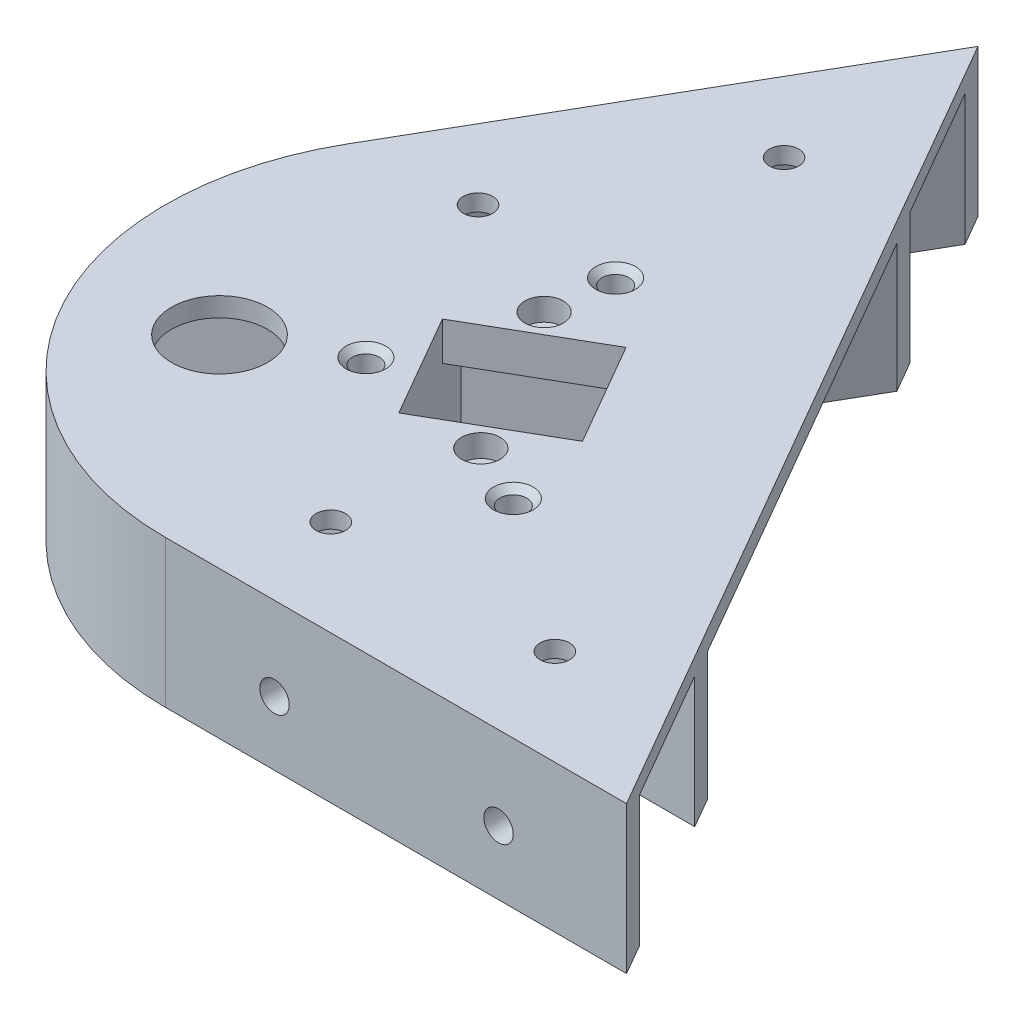
SolidWorks part; units mm, degrees
other "Markup1"
sketch "Sketch26" plane through (25.6218, 0, -129.9038) normal (-0.1134, -0.9932, -0.0259) x (0.9576, -0.1162, 0.2636)
ref_plane "Front Plane" through (0, 0, 0) normal (0, 0, 1) x (1, 0, 0)
ref_plane "Top Plane" through (0, 0, 0) normal (0, 1, 0) x (1, 0, 0)
ref_plane "Right Plane" through (0, 0, 0) normal (1, 0, 0) x (0, 0, -1)
sketch "Sketch1" plane through (0, 0, 0) normal (0, 1, 0) x (1, 0, 0)
  line L0 (0, 0) -> (150, 0)
  line L1 (0, 0) -> (75, 129.9038)
  line L2 (75, 129.9038) -> (150, 0)
  dimension "D1" = 60
  dimension "D2" = 150
  dimension "D3" = 60
extrude "Boss-Extrude1" add sketch "Sketch1" along normal blind 23
sketch "Sketch2" plane through (0, 0, 0) normal (0, 1, 0) x (1, 0, 0)
  line L0 (0, 0) -> (150, 0) construction
  line L1 (74, 5) -> (174, 5) construction
  line L2 (74, 5) -> (74, 25) construction
  line L3 (74, 25) -> (174, 25) construction
  line L4 (174, 5) -> (174, 25) construction
  line L5 (41.3301, 61.5859) -> (91.3301, 148.1884) construction
  line L6 (91.3301, 148.1884) -> (108.6506, 138.1884) construction
  line L7 (108.6506, 138.1884) -> (58.6506, 51.5859) construction
  line L8 (58.6506, 51.5859) -> (41.3301, 61.5859) construction
  line L9 (75, 129.9038) -> (0, 0) construction
  line L10 (108.9238, 138.2616) -> (58.7238, 51.3127)
  line L11 (58.7238, 51.3127) -> (41.0569, 61.5127)
  line L12 (41.0569, 61.5127) -> (91.2569, 148.4616)
  line L13 (91.2569, 148.4616) -> (108.9238, 138.2616)
  line L14 (73.8, 25.2) -> (174.2, 25.2)
  line L15 (174.2, 4.8) -> (174.2, 25.2)
  line L16 (73.8, 4.8) -> (174.2, 4.8)
  line L17 (73.8, 4.8) -> (73.8, 25.2)
  dimension "D1" = 20
  dimension "D2" = 5
  dimension "D3" = 74
  dimension "D4" = 20
  dimension "D5" = 74
  dimension "D6" = 5
  dimension "D7" = 100
  dimension "D8" = 100
  dimension "D9" = 0.2
  dimension "D10" = 0.2
extrude "Cut-Extrude2" cut sketch "Sketch2" along normal blind 20.4
sketch "Sketch4" plane through (0, 0, 0) normal (0, 1, 0) x (1, 0, 0)
  line L4 (135.4508, 25.2) -> (89.5492, 104.7038) construction
  line L5 (41.1219, 35.2887) -> (0, 0) construction
  line L6 (0, 0) -> (52.9457, 91.7047) construction
  line L7 (68.4424, 27.9682) -> (51.1219, 17.9682) construction
  line L8 (68.4424, 27.9682) -> (58.4424, 45.2887) construction
  line L9 (58.4424, 45.2887) -> (41.1219, 35.2887) construction
  line L10 (51.1219, 17.9682) -> (41.1219, 35.2887) construction
  line L11 (68.4424, 27.9682) -> (41.1219, 35.2887) construction
  line L12 (58.4424, 45.2887) -> (51.1219, 17.9682) construction
  line L13 (58.5156, 45.5619) -> (40.8487, 35.3619)
  line L14 (75, 129.9038) -> (0, 0) construction
  line L15 (0, 0) -> (130.8784, 0) construction
  line L16 (0, 0) -> (150, 0) construction
  line L17 (51.0487, 17.695) -> (40.8487, 35.3619)
  line L18 (68.7156, 27.895) -> (51.0487, 17.695)
  line L19 (68.7156, 27.895) -> (58.5156, 45.5619)
  line L20 (51.1219, 17.9682) -> (0, 0) construction
  point P0 (54.7821, 31.6285)
  dimension "D1" = 20
  dimension "D2" = 20
  dimension "D3" = 21.269
  dimension "D4" = 0.2
  dimension "D5" = 54.1877
  dimension "D6" = 19.365
extrude "Cut-Extrude3" cut sketch "Sketch4" along normal blind 20
sketch "Sketch7" plane through (0, 0, 0) normal (-0.866, 0, -0.5) x (-0.5, 0, 0.866)
  line L0 (-150, 0) -> (0, 0) construction
  line L1 (-150, 23) -> (-150, 0) construction
  circle A0 centre (-130, 10) radius 2.3
  circle A1 centre (-95, 10) radius 2.3
  dimension "D1" = 4.6
  dimension "D2" = 10
  dimension "D3" = 20
  dimension "D4" = 35
extrude "Cut-Extrude6" cut sketch "Sketch7" against normal blind 10
sketch "Sketch8" plane through (0, 0, 0) normal (0, 0, 1) x (1, 0, 0)
  line L0 (150, 23) -> (150, 0) construction
  line L1 (0, 0) -> (150, 0) construction
  circle A0 centre (130, 10) radius 2.3
  circle A1 centre (95, 10) radius 2.3
  dimension "D1" = 4.6
  dimension "D2" = 20
  dimension "D3" = 10
  dimension "D4" = 35
extrude "Cut-Extrude7" cut sketch "Sketch8" against normal blind 10
ref_plane "Plane1" through (42.4846, 0, -24.5285) normal (0.866, 0, -0.5) x (-0.5, 0, -0.866)
fillet "Fillet3" radius 45 1 edges at (0, 11.5, 0)
sketch "Sketch22" plane through (0, 0, 0) normal (0, -1, 0) x (1, 0, 0)
  line L0 (83.3534, -28.1478) -> (66.0534, -58.1122)
  line L1 (66.0534, -58.1122) -> (84.2399, -68.6122)
  line L2 (84.2399, -68.6122) -> (101.5399, -38.6478)
  line L3 (101.5399, -38.6478) -> (83.3534, -28.1478)
  line L5 (135.4508, -25.2) -> (89.5492, -104.7038) construction
  dimension "D1" = 86.26
  dimension "D2" = 17.3
  dimension "D3" = 17.3
  dimension "D4" = 21
extrude "Cut-Extrude11" cut sketch "Sketch22" against normal through all both and the other way through all
sketch "Sketch21" plane through (0, 0, 0) normal (0, -1, 0) x (1, 0, 0)
  line L0 (132.6795, -30) -> (109.9968, -30)
  line L1 (109.9968, -30) -> (80.9791, -80.26)
  line L2 (80.9791, -80.26) -> (92.3205, -99.9038)
  line L3 (92.3205, -99.9038) -> (132.6795, -30)
  line L4 (135.4508, -25.2) -> (89.5492, -104.7038) construction
  line L5 (135.4508, -25.2) -> (73.8, -25.2) construction
  line L7 (58.7238, -51.3127) -> (89.5492, -104.7038) construction
  line L8 (58.7238, -51.3127) -> (89.5492, -104.7038) construction
  line L9 (84.2399, -68.6122) -> (101.5399, -38.6478) construction
  dimension "D1" = 3
  dimension "D2" = 4.8
  dimension "D3" = 4.8
extrude "Cut-Extrude10" cut sketch "Sketch21" against normal offset from surface (20 mm away) 3 up to face at (83.7966, 23, -48.38)
sketch "Sketch32" plane through (0, 0, -30) normal (0, 0, -1) x (-1, 0, 0)
  line L0 (-132.6795, 10) -> (-109.9968, 10) construction
  line L1 (-132.6795, 20) -> (-132.6795, 0) construction
  line L2 (-109.9968, 20) -> (-109.9968, 0) construction
  circle A0 centre (-121.3381, 10) radius 2.3
  dimension "D1" = 4.6
extrude "Cut-Extrude18" cut sketch "Sketch32" against normal blind 10
sketch "Sketch33" plane through (25.9808, 0, 15) normal (0.866, 0, 0.5) x (0.5, 0, -0.866)
  line L0 (109.9968, 10) -> (132.6795, 10) construction
  line L1 (109.9968, 20) -> (109.9968, 0) construction
  line L2 (132.6795, 20) -> (132.6795, 0) construction
  circle A0 centre (121.3381, 10) radius 2.3
  dimension "D1" = 4.6
extrude "Cut-Extrude19" cut sketch "Sketch33" against normal blind 10
sketch "Sketch34" plane through (45.9487, 0, -26.5285) normal (0.866, 0, -0.5) x (-0.5, 0, -0.866)
  line L0 (-10.2, 10) -> (10.2, 10) construction
  line L1 (-10.2, 20) -> (-10.2, 0) construction
  line L2 (10.2, 20) -> (10.2, 0) construction
  circle A0 centre (0, 10) radius 2.3
  dimension "D1" = 4.6
extrude "Cut-Extrude20" cut sketch "Sketch34" against normal through all
ref_plane "Plane2" through (43.3506, 0, -25.0285) normal (0.866, 0, -0.5) x (-0.5, 0, -0.866)
sketch "Sketch35" plane through (43.3506, 0, -25.0285) normal (0.866, 0, -0.5) x (-0.5, 0, -0.866)
  circle A0 centre (0, 10) radius 4
  dimension "D1" = 8
extrude "Cut-Extrude21" cut sketch "Sketch35" against normal through all
sketch "Sketch36" plane through (0, 23, 0) normal (0, 1, 0) x (1, 0, 0)
  line L0 (0, 0) -> (112.5, 64.9519) construction
  line L1 (150, 0) -> (75, 129.9038) construction
  circle A0 centre (69.282, 40) radius 2.1
  dimension "D1" = 4.2
  dimension "D2" = 80
extrude "Cut-Extrude22" cut sketch "Sketch36" against normal through all
sketch "Sketch38" plane through (0, 20.4, 0) normal (0, -1, 0) x (1, 0, 0)
  line L0 (49.8904, -56.4127) -> (83.6603, -114.9038) construction
  line L1 (41.0569, -61.5127) -> (58.7238, -51.3127) construction
  line L2 (77.7713, -125.1038) -> (89.5492, -104.7038) construction
  line L3 (73.8, -15) -> (141.3397, -15) construction
  line L4 (73.8, -25.2) -> (73.8, -4.8) construction
  line L5 (135.4508, -25.2) -> (147.2287, -4.8) construction
  line L6 (41.0569, -61.5127) -> (58.7238, -51.3127) construction
  circle A0 centre (88.8, -15) radius 2.3
  circle A1 centre (123.8, -15) radius 2.3
  circle A2 centre (57.3904, -69.4031) radius 2.3
  circle A3 centre (74.8904, -99.7139) radius 2.3
  dimension "D1" = 4.6
  dimension "D2" = 15
  dimension "D3" = 35
  dimension "D4" = 15
  dimension "D5" = 35
extrude "Cut-Extrude24" cut sketch "Sketch38" against normal blind 10
sketch "Sketch39" plane through (0, 23, 0) normal (0, 1, 0) x (1, 0, 0)
  line L0 (66.0534, 58.1122) -> (84.2399, 68.6122)
  line L1 (84.2399, 68.6122) -> (88.2399, 61.684)
  line L2 (84.2399, 68.6122) -> (101.5399, 38.6478) construction
  line L3 (88.2399, 61.684) -> (70.0534, 51.184)
  line L4 (83.3534, 28.1478) -> (66.0534, 58.1122) construction
  line L5 (70.0534, 51.184) -> (66.0534, 58.1122)
  line L6 (101.5399, 38.6478) -> (83.3534, 28.1478)
  line L7 (83.3534, 28.1478) -> (79.3534, 35.076)
  line L8 (79.3534, 35.076) -> (97.5399, 45.576)
  line L9 (97.5399, 45.576) -> (101.5399, 38.6478)
  dimension "D1" = 8
  dimension "D2" = 8
extrude "Boss-Extrude2" add sketch "Sketch39" against normal blind 6
sketch "Sketch40" plane through (0, 17, 0) normal (0, -1, 0) x (1, 0, 0)
  line L0 (92.4466, -33.3978) -> (75.1466, -63.3622) construction
  line L1 (101.5399, -38.6478) -> (83.3534, -28.1478) construction
  line L2 (66.0534, -58.1122) -> (84.2399, -68.6122) construction
  line L3 (84.2399, -68.6122) -> (66.0534, -58.1122) construction
  circle A0 centre (90.5466, -36.6887) radius 1.65
  circle A1 centre (77.0466, -60.0713) radius 1.65
  dimension "D1" = 3.3
  dimension "D2" = 3.3
  dimension "D3" = 3.8
  dimension "D4" = 3.8
extrude "Cut-Extrude25" cut sketch "Sketch40" against normal through all
sketch "Sketch41" plane through (0, 23, 0) normal (0, 1, 0) x (1, 0, 0)
  circle A0 centre (77.0466, 60.0713) radius 3
  circle A1 centre (90.5466, 36.6887) radius 3
  dimension "D1" = 6
extrude "Cut-Extrude26" cut sketch "Sketch41" against normal blind 3.5
sketch "Sketch42" plane through (0, 23, 0) normal (0, 1, 0) x (1, 0, 0)
  line L0 (0, 0) -> (98.694, 88.8645) construction
  line L1 (150, 0) -> (75, 129.9038) construction
  line L2 (0, 0) -> (126.306, 41.0393) construction
  line L3 (0, 0) -> (112.5, 64.9519) construction
  line L4 (132.6795, 30) -> (92.3205, 99.9038) construction
  circle A0 centre (99.8609, 32.4468) radius 2.1
  circle A1 centre (78.0302, 70.2587) radius 2.1
  dimension "D5" = 4.2
  dimension "D1" = 12
  dimension "D2" = 12
  dimension "D3" = 105
  dimension "D4" = 105
extrude "Cut-Extrude27" cut sketch "Sketch42" against normal through all
chamfer "Chamfer2" distance 1 angle 45 3 edges at (78.0302, 23, -68.1587) (69.282, 23, -37.9) (99.8609, 23, -30.3468)
sketch "Sketch43" plane through (0, 0, 0) normal (0, -1, 0) x (1, 0, 0)
  line L0 (59.8821, -22.795) -> (49.6821, -40.4619) construction
  line L3 (51.0487, -17.695) -> (68.7156, -27.895) construction
  line L4 (58.5156, -45.5619) -> (40.8487, -35.3619) construction
  line L5 (49.6821, -40.4619) -> (59.8821, -22.795) construction
  line L6 (58.5156, -45.5619) -> (40.8487, -35.3619) construction
  circle A0 centre (64.3821, -15.0008) radius 2.1
  circle A1 centre (45.1821, -48.2562) radius 2.1
  point P7 (54.7821, -31.6285)
  dimension "D1" = 4.2
  dimension "D2" = 9
  dimension "D3" = 9
extrude "Cut-Extrude28" cut sketch "Sketch43" against normal blind 15
chamfer "Chamfer3" distance 1 angle 45 2 edges at (64.3821, 0, -17.1008) (45.1821, 0, -50.3562)
ref_plane "Plane3" through (66.2137, 0, -38.2285) normal (-0.866, 0, 0.5) x (0.5, 0, 0.866)
sketch "Sketch45" plane through (63.6156, 0, -36.7285) normal (-0.866, 0, 0.5) x (0.5, 0, 0.866)
  line L0 (-10.2, 10) -> (10.2, 10) construction
  line L1 (-10.2, 20) -> (-10.2, 0) construction
  line L2 (10.2, 20) -> (10.2, 0) construction
  circle A0 centre (0, 10) radius 2.3
  dimension "D1" = 4.6
extrude "Cut-Extrude29" cut sketch "Sketch45" against normal through all
sketch "Sketch46" plane through (66.2137, 0, -38.2285) normal (-0.866, 0, 0.5) x (0.5, 0, 0.866)
  circle A0 centre (0, 10) radius 4
extrude "Cut-Extrude30" cut sketch "Sketch46" against normal through all
sketch "Sketch47" plane through (0, 20, 0) normal (0, -1, 0) x (1, 0, 0)
  line L0 (59.8821, -22.795) -> (49.6821, -40.4619) construction
  line L1 (51.0487, -17.695) -> (68.7156, -27.895) construction
  line L2 (58.5156, -45.5619) -> (40.8487, -35.3619) construction
  line L3 (45.9487, -26.5285) -> (63.6156, -36.7285) construction
  line L4 (40.8487, -35.3619) -> (51.0487, -17.695) construction
  line L5 (68.7156, -27.895) -> (58.5156, -45.5619) construction
  circle A0 centre (54.7821, -31.6285) radius 7.5
  dimension "D1" = 15
extrude "Cut-Extrude31" cut sketch "Sketch47" against normal blind 10
